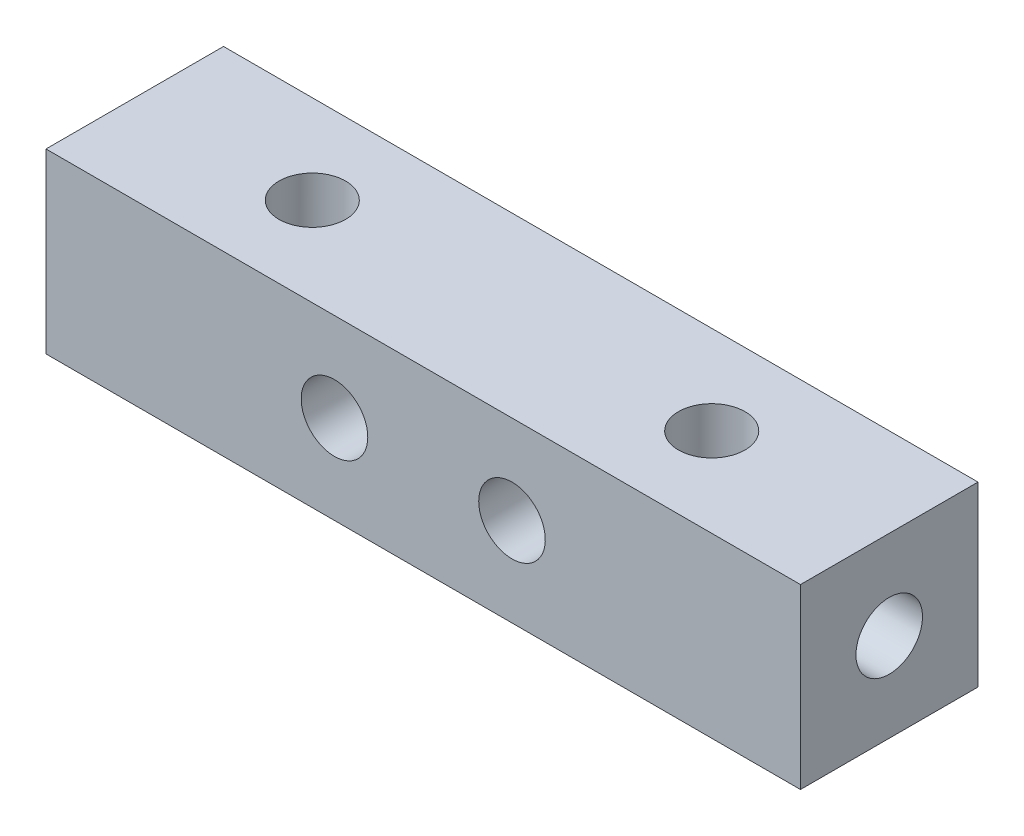
SolidWorks part; units mm, degrees
material "AISI 304"
ref_plane "前视基准面" through (0, 0, 0) normal (0, 0, 1) x (1, 0, 0)
ref_plane "上视基准面" through (0, 0, 0) normal (0, 1, 0) x (1, 0, 0)
ref_plane "右视基准面" through (0, 0, 0) normal (1, 0, 0) x (0, 0, -1)
other "Configuration Table"
sketch "草图1" plane through (0, 0, 0) normal (0, 1, 0) x (1, 0, 0)
  line L1 (-17, -4) -> (17, -4)
  line L2 (-17, -4) -> (-17, 4)
  line L3 (-17, 4) -> (17, 4)
  line L4 (17, -4) -> (17, 4)
  line L5 (-17, -4) -> (17, 4) construction
  line L6 (-17, 4) -> (17, -4) construction
  circle A0 centre (-9, 0) radius 1.5
  circle A1 centre (9, 0) radius 1.5
  point P0 (0, 0)
  dimension "D3" = 3
  dimension "D4" = 3
  dimension "D5" = 18
  dimension "D6" = 8
  dimension "D8" = 4
  dimension "D1" = 34
  dimension "D2" = 8
  dimension "D7" = 4
extrude "凸台-拉伸1" add sketch "草图1" along normal blind 8
sketch "草图2" plane through (0, 0, 4) normal (0, 0, 1) x (1, 0, 0)
  line L0 (0, 0) -> (0, 13.2002) construction
  line L1 (-17, 8) -> (17, 8) construction
  circle A0 centre (-4, 4) radius 1.5
  circle A1 centre (4, 4) radius 1.5
  dimension "D1" = 3
  dimension "D2" = 4
  dimension "D3" = 8
extrude "切除-拉伸1" cut sketch "草图2" against normal blind 8
sketch "草图3" plane through (-17, 0, 0) normal (-1, 0, 0) x (0, 0, 1)
  line L0 (-4, 8) -> (-4, 0) construction
  line L1 (-4, 0) -> (4, 0) construction
  circle A0 centre (0, 4) radius 1.5
  dimension "D1" = 3
  dimension "D2" = 4
  dimension "D3" = 4
extrude "切除-拉伸2" cut sketch "草图3" against normal blind 39
